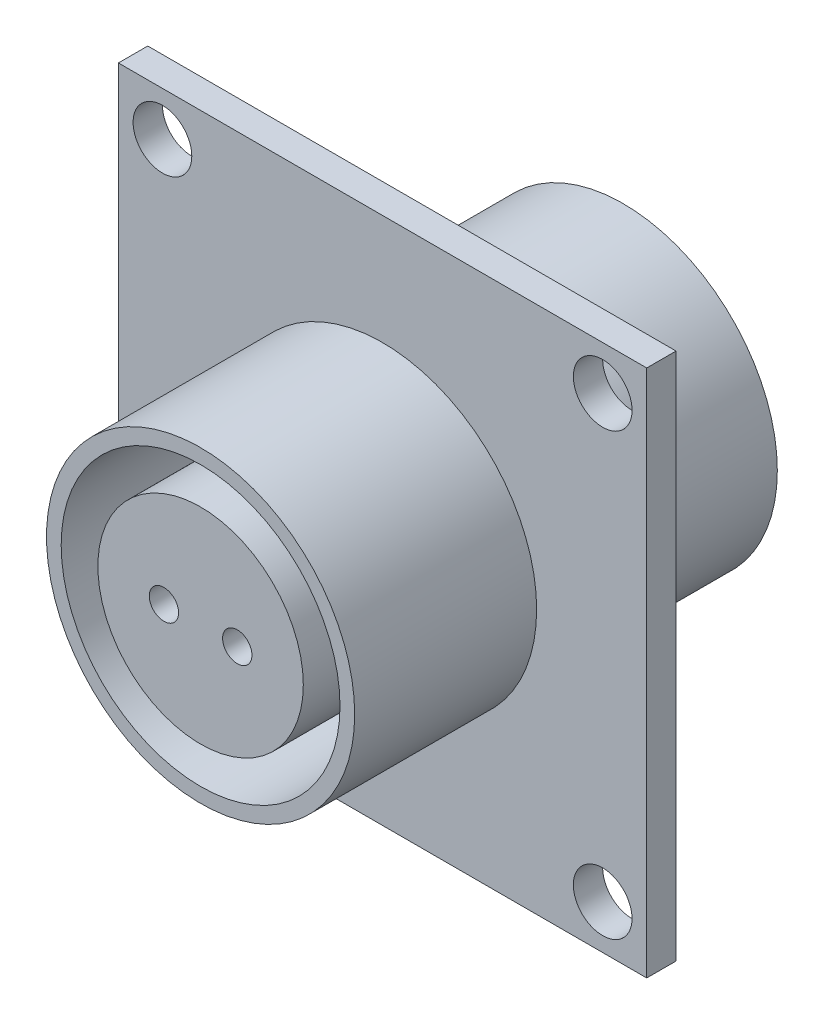
SolidWorks part; units mm, degrees
ref_plane "前视基准面" through (0, 0, 0) normal (0, 0, 1) x (1, 0, 0)
ref_plane "上视基准面" through (0, 0, 0) normal (0, 1, 0) x (1, 0, 0)
ref_plane "右视基准面" through (0, 0, 0) normal (1, 0, 0) x (0, 0, -1)
sketch "草图1" plane through (0, 0, 0) normal (0, 0, 1) x (1, 0, 0)
  line L13 (-3, 3) -> (33, 3)
  line L14 (-3, 3) -> (-3, -33)
  line L15 (-3, -33) -> (33, -33)
  line L16 (33, 3) -> (33, -33)
  circle A0 centre (0, 0) radius 2
  circle A1 centre (0, -30) radius 2
  circle A2 centre (30, -30) radius 2
  circle A4 centre (30, 0) radius 2
  dimension "D1" = 2
extrude "凸台-拉伸1" add sketch "草图1" along normal blind 2
sketch "草图2" plane through (0, 0, 2) normal (0, 0, 1) x (1, 0, 0)
  circle A0 centre (15, -15) radius 10.5
extrude "凸台-拉伸2" add sketch "草图2" along normal blind 12.4 and the other way blind 16.4
sketch "草图3" plane through (0, 0, 14.4) normal (0, 0, 1) x (1, 0, 0)
  circle A0 centre (15, -15) radius 7
  circle A1 centre (15, -15) radius 9.5
  circle A2 centre (17.5, -15) radius 1
  circle A3 centre (12.5, -15) radius 1
extrude "切除-拉伸1" cut sketch "草图3" against normal blind 10 contours A1 A0 | A2 | A3
